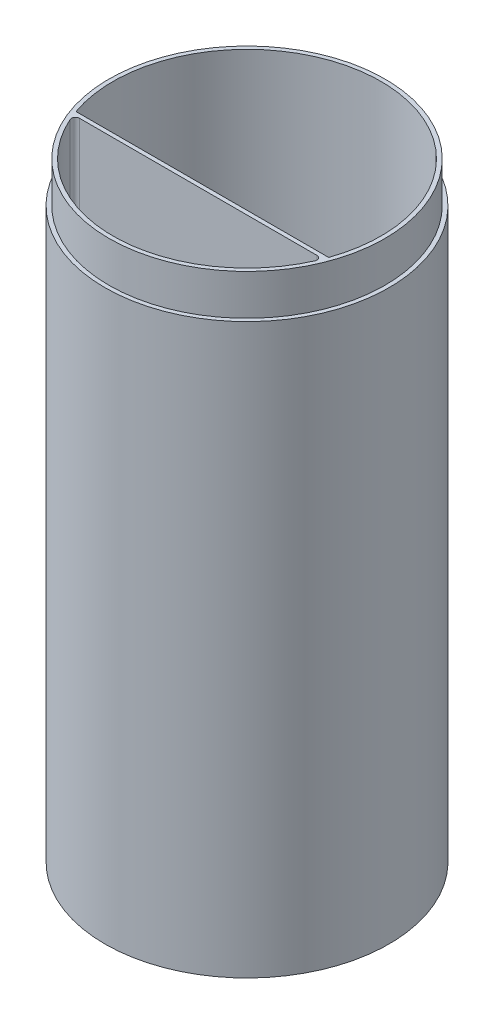
SolidWorks part; units mm, degrees
ref_plane "Front Plane" through (0, 0, 0) normal (0, 0, 1) x (1, 0, 0)
ref_plane "Top Plane" through (0, 0, 0) normal (0, 1, 0) x (1, 0, 0)
ref_plane "Right Plane" through (0, 0, 0) normal (1, 0, 0) x (0, 0, -1)
sketch "Sketch1" plane through (0, 0, 0) normal (0, 1, 0) x (1, 0, 0)
  line L0 (-31.4484, -10) -> (31.4484, -10)
  line L1 (-30.7409, -12) -> (30.7409, -12)
  arc A0 (31.4484, -10) -> (-31.4484, -10) centre (0, 0) ccw
  circle A1 centre (0, 0) radius 35
  arc A2 (30.7409, -12) -> (31.4484, -10) centre (0, 0) ccw construction
  circle A3 centre (0, 0) radius 33 construction
  arc A4 (-31.4484, -10) -> (-30.7409, -12) centre (0, 0) ccw construction
  arc A5 (-30.7409, -12) -> (30.7409, -12) centre (0, 0) ccw
  dimension "D2" = 70
  dimension "D3" = 2
  dimension "D4" = 10
  dimension "D1" = 2
extrude "Boss-Extrude1" add sketch "Sketch1" along normal blind 150
fillet "Fillet1" radius 1 4 edges at (-31.4484, 75, 10) (31.4484, 75, 10) (-30.7409, 75, 12) (30.7409, 75, 12)
sketch "Sketch3" plane through (0, 150, 0) normal (0, 1, 0) x (1, 0, 0)
  line L0 (33, 0) -> (35, 0) construction
  line L1 (-30.7083, -10) -> (30.7083, -10) construction
  line L2 (-30.7083, -10) -> (30.7083, -10)
  line L3 (-31.1127, -11) -> (31.1127, -11)
  line L4 (0, -10) -> (0, -12) construction
  line L5 (29.2404, -12) -> (-29.2404, -12) construction
  circle A0 centre (0, 0) radius 34
  arc A3 (31.6679, -9.2813) -> (-31.6679, -9.2813) centre (0, 0) ccw construction
  circle A4 centre (0, 0) radius 35 construction
  circle A5 centre (0, 0) radius 35
  arc A6 (-31.6679, -9.2813) -> (-31.1127, -11) centre (0, 0) ccw
  arc A7 (30.7083, -10) -> (31.6679, -9.2813) centre (30.7083, -9) ccw construction
  arc A8 (-31.6679, -9.2813) -> (-30.7083, -10) centre (-30.7083, -9) ccw construction
  arc A9 (30.7083, -10) -> (31.6679, -9.2813) centre (30.7083, -9) ccw
  arc A10 (-31.6679, -9.2813) -> (-30.7083, -10) centre (-30.7083, -9) ccw
  arc A11 (33, 0) -> (-31.6679, -9.2813) centre (0, 0) ccw construction
  arc A12 (-31.1127, -11) -> (31.1127, -11) centre (0, 0) ccw construction
  arc A13 (31.1127, -11) -> (33, 0) centre (0, 0) ccw
  point P3 (34, 0)
  point P21 (0, -11)
  circle M5 centre (0, 0) radius 35
  line M6 (30.7083, -10) -> (-30.7083, -10)
  arc M7 (-30.7083, -10) -> (-31.6679, -9.2813) centre (-30.7083, -9) cw
  arc M9 (31.6679, -9.2813) -> (30.7083, -10) centre (30.7083, -9) cw
extrude "Cut-Extrude1" cut sketch "Sketch3" against normal blind 10 contours A0 M5 | L3 A13 A6 M9 M6 M7
sketch "Sketch4" plane through (0, 0, 0) normal (0, -1, 0) x (1, 0, 0)
  line L0 (-11, 0) -> (11, 0) construction
  line L1 (-30.7083, 10) -> (30.7083, 10) construction
  line L2 (-23.25, 10) -> (23.25, 10)
  line L3 (-23.25, 0) -> (-23.25, 10)
  line L4 (23.25, 0) -> (23.25, 10)
  line L5 (-3, 4.6435) -> (3, 4.6435)
  line L6 (-11, -12.25) -> (11, -12.25) construction
  line L8 (-3, -4.6435) -> (3, -4.6435)
  line L9 (0, -7.5) -> (0, 7.5) construction
  line L10 (-20.5, 7.5) -> (20.5, 7.5) construction
  line L11 (-11, -12.25) -> (-7.5, -10.75)
  line L12 (-7.5, -10.75) -> (7.5, -10.75)
  line L13 (7.5, -10.75) -> (11, -12.25)
  arc A0 (-3, 4.6435) -> (-3, -4.6435) centre (-11, 0) ccw
  arc A1 (3, -4.6435) -> (3, 4.6435) centre (11, 0) ccw
  arc A2 (-23.25, 0) -> (-11, -12.25) centre (-11, 0) ccw
  arc A3 (11, -12.25) -> (23.25, 0) centre (11, 0) ccw
  circle A4 centre (0, -7.5) radius 2.25
  circle A5 centre (20.5, 7.5) radius 2.25
  circle A6 centre (-20.5, 7.5) radius 2.25
  circle A7 centre (0, 7.5) radius 2.25
  point P4 (0, 0)
  point P24 (0, 0)
  point P25 (0, 7.5)
  point P26 (0, -10.75)
  dimension "D1" = 18.5
  dimension "D4" = 3
  dimension "D5" = 4.5
  dimension "D2" = 22
  dimension "D3" = 6
  dimension "D6" = 15
  dimension "D7" = 41
  dimension "D8" = 15
  dimension "D9" = 1.5
extrude "Boss-Extrude2" add sketch "Sketch4" against normal blind 6 from offset 5 offset against normal yes
sketch "Sketch5" plane through (0, 11, 0) normal (0, 1, 0) x (1, 0, 0)
  line L0 (3, -4.6435) -> (-3, -4.6435) construction
  line L1 (-3, 4.6435) -> (3, 4.6435) construction
  line L2 (3, -4.6435) -> (-3, -4.6435)
  line L3 (-3, 4.6435) -> (3, 4.6435)
  line L6 (-23.25, 0) -> (-23.25, -10)
  line L7 (-23.25, -10) -> (23.25, -10)
  line L8 (23.25, -10) -> (23.25, 0)
  line L9 (11, 12.25) -> (7.5, 10.75)
  line L10 (7.5, 10.75) -> (-7.5, 10.75)
  line L11 (-7.5, 10.75) -> (-11, 12.25)
  line L12 (-23.25, 0) -> (-23.25, -10)
  line L13 (-23.25, -10) -> (23.25, -10)
  line L14 (23.25, -10) -> (23.25, 0)
  line L15 (11, 12.25) -> (7.5, 10.75)
  line L16 (7.5, 10.75) -> (-7.5, 10.75)
  line L17 (-7.5, 10.75) -> (-11, 12.25)
  arc A0 (3, -4.6435) -> (3, 4.6435) centre (11, 0) ccw construction
  arc A1 (-3, 4.6435) -> (-3, -4.6435) centre (-11, 0) ccw construction
  arc A2 (-11, 12.25) -> (-23.25, 0) centre (-11, 0) ccw
  arc A3 (23.25, 0) -> (11, 12.25) centre (11, 0) ccw
  arc A4 (-11, 12.25) -> (-23.25, 0) centre (-11, 0) ccw
  arc A5 (23.25, 0) -> (11, 12.25) centre (11, 0) ccw
  arc A6 (3, -4.6435) -> (3, 4.6435) centre (11, 0) ccw
  arc A7 (-3, 4.6435) -> (-3, -4.6435) centre (-11, 0) ccw
  dimension "D1" = 0
extrude "Boss-Extrude3" add sketch "Sketch5" along normal blind 64
